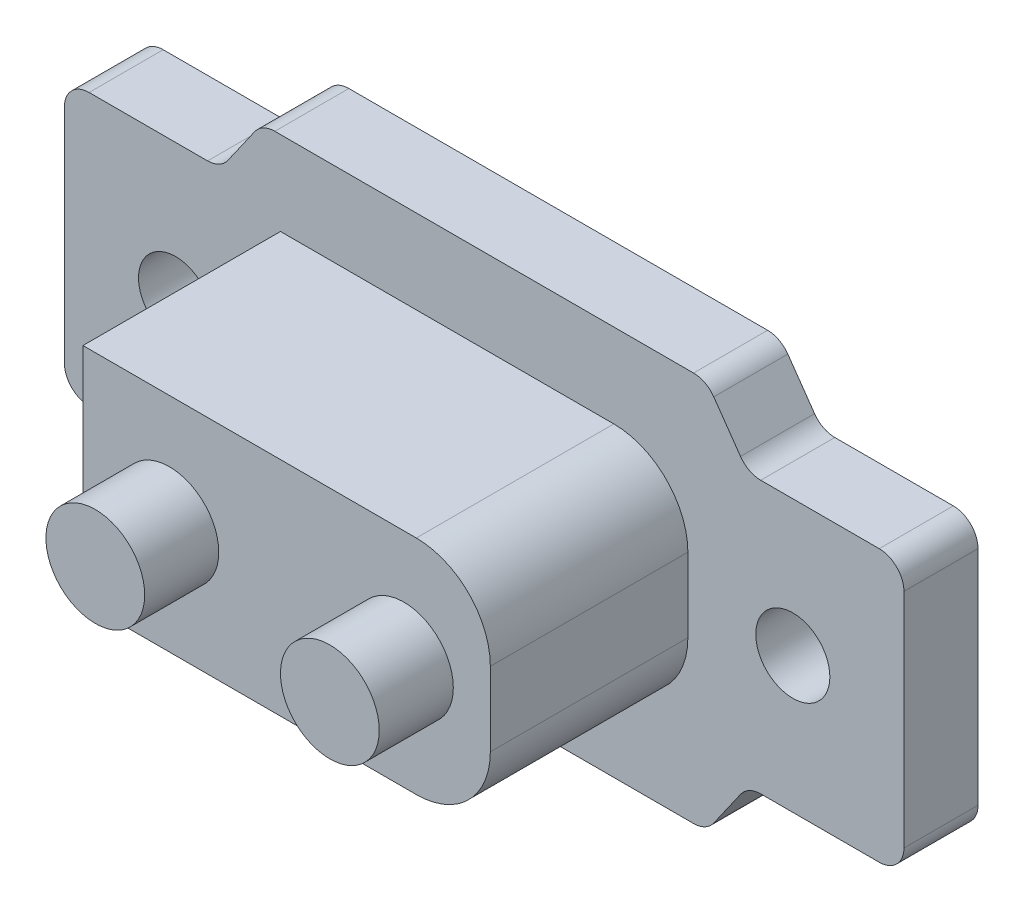
SolidWorks part; units mm, degrees
ref_plane "Front Plane" through (0, 0, 0) normal (0, 0, 1) x (1, 0, 0)
ref_plane "Top Plane" through (0, 0, 0) normal (0, 1, 0) x (1, 0, 0)
ref_plane "Right Plane" through (0, 0, 0) normal (1, 0, 0) x (0, 0, -1)
sketch "Sketch1" plane through (0, 0, 0) normal (0, 0, 1) x (1, 0, 0)
  line L1 (54.8017, 41.1928) -> (88.8017, 41.1928)
  line L2 (54.8017, 41.1928) -> (54.8017, 25.3928)
  line L3 (54.8017, 25.3928) -> (88.8017, 25.3928)
  line L4 (88.8017, 41.1928) -> (88.8017, 25.3928)
  dimension "D1" = 15.8
  dimension "D2" = 34
extrude "Boss-Extrude1" add sketch "Sketch1" along normal blind 3
sketch "Sketch2" plane through (0, 0, 3) normal (0, 0, 1) x (1, 0, 0)
  line L0 (54.8017, 33.2928) -> (88.8017, 33.2928) construction
  line L1 (54.8017, 41.1928) -> (54.8017, 25.3928) construction
  line L2 (88.8017, 25.3928) -> (88.8017, 41.1928) construction
  line L3 (71.8017, 41.1928) -> (71.8017, 25.3928) construction
  line L4 (88.8017, 41.1928) -> (54.8017, 41.1928) construction
  line L5 (54.8017, 25.3928) -> (88.8017, 25.3928) construction
  line L7 (63.5517, 37.7928) -> (77.0517, 37.7928)
  line L8 (63.5517, 37.7928) -> (63.5517, 28.7928)
  line L9 (63.5517, 28.7928) -> (77.0517, 28.7928)
  line L10 (80.0517, 34.7928) -> (80.0517, 31.7928)
  arc A0 (77.0517, 28.7928) -> (80.0517, 31.7928) centre (77.0517, 31.7928) ccw
  arc A1 (77.0517, 37.7928) -> (80.0517, 34.7928) centre (77.0517, 34.7928) cw
  point P18 (80.0517, 28.7928)
  point P21 (80.0517, 37.7928)
  dimension "D5" = 3
  dimension "D1" = 9
  dimension "D2" = 16.5
  dimension "D3" = 8.25
  dimension "D4" = 4.5
extrude "Boss-Extrude2" add sketch "Sketch2" along normal blind 8
sketch "Sketch3" plane through (0, 0, 3) normal (0, 0, 1) x (1, 0, 0)
  line L0 (54.8017, 33.2928) -> (88.8017, 33.2928) construction
  line L1 (54.8017, 41.1928) -> (62.8017, 41.1928)
  line L2 (54.8017, 41.1928) -> (54.8017, 38.7928)
  line L3 (54.8017, 38.7928) -> (61.1212, 38.7928)
  line L5 (54.8017, 41.1928) -> (54.8017, 25.3928) construction
  line L6 (88.8017, 25.3928) -> (88.8017, 41.1928) construction
  line L7 (62.8017, 41.1928) -> (61.1212, 38.7928)
  line L8 (71.8017, 41.1928) -> (71.8017, 25.3928) construction
  line L9 (88.8017, 41.1928) -> (54.8017, 41.1928) construction
  line L10 (54.8017, 25.3928) -> (88.8017, 25.3928) construction
  line L11 (62.8017, 25.3928) -> (61.1212, 27.7928)
  line L12 (54.8017, 27.7928) -> (61.1212, 27.7928)
  line L13 (54.8017, 25.3928) -> (54.8017, 27.7928)
  line L14 (54.8017, 25.3928) -> (62.8017, 25.3928)
  line L15 (88.8017, 25.3928) -> (80.8017, 25.3928)
  line L16 (88.8017, 25.3928) -> (88.8017, 27.7928)
  line L17 (88.8017, 27.7928) -> (82.4822, 27.7928)
  line L18 (80.8017, 25.3928) -> (82.4822, 27.7928)
  line L19 (80.8017, 41.1928) -> (82.4822, 38.7928)
  line L20 (88.8017, 38.7928) -> (82.4822, 38.7928)
  line L21 (88.8017, 41.1928) -> (88.8017, 38.7928)
  line L22 (88.8017, 41.1928) -> (80.8017, 41.1928)
  dimension "D1" = 5.5
  dimension "D2" = 8
  dimension "D3" = 55
extrude "Cut-Extrude1" cut sketch "Sketch3" against normal through all
sketch "Sketch4" plane through (0, 0, 11) normal (0, 0, 1) x (1, 0, 0)
  line L0 (71.8017, 41.1928) -> (71.8017, 25.3928) construction
  line L1 (80.8017, 41.1928) -> (62.8017, 41.1928) construction
  line L2 (62.8017, 25.3928) -> (80.8017, 25.3928) construction
  circle A0 centre (67.0517, 33.2928) radius 2
  circle A1 centre (76.5517, 33.2928) radius 2
  dimension "D1" = 4
  dimension "D2" = 4.75
  dimension "D3" = 4.75
extrude "Boss-Extrude3" add sketch "Sketch4" along normal blind 3
fillet "Fillet1" radius 1 12 edges at (88.8017, 38.7928, 1.5) (82.4822, 38.7928, 1.5) (80.8017, 41.1928, 1.5) (88.8017, 27.7928, 1.5) (82.4822, 27.7928, 1.5) (80.8017, 25.3928, 1.5) (62.8017, 25.3928, 1.5) (61.1212, 27.7928, 1.5) (54.8017, 27.7928, 1.5) (62.8017, 41.1928, 1.5) (61.1212, 38.7928, 1.5) (54.8017, 38.7928, 1.5)
sketch "Sketch5" plane through (0, 0, 3) normal (0, 0, 1) x (1, 0, 0)
  line L0 (71.8017, 41.1928) -> (71.8017, 25.3928) construction
  line L1 (80.2811, 41.1928) -> (63.3223, 41.1928) construction
  line L2 (63.3223, 25.3928) -> (80.2811, 25.3928) construction
  circle A0 centre (59.3017, 33.2928) radius 1.5
  circle A1 centre (84.3017, 33.2928) radius 1.5
extrude "Cut-Extrude2" cut sketch "Sketch5" against normal through all
sketch "Sketch6" plane through (0, 0, 0) normal (0, 0, -1) x (-1, 0, 0)
  line L0 (-71.8017, 41.1928) -> (-71.8017, 25.3928) construction
  line L1 (-77.8017, 36.7928) -> (-65.8017, 36.7928)
  line L2 (-79.8017, 34.7928) -> (-79.8017, 31.7928)
  line L3 (-77.8017, 29.7928) -> (-65.8017, 29.7928)
  line L4 (-63.8017, 34.7928) -> (-63.8017, 31.7928)
  line L5 (-80.2811, 41.1928) -> (-63.3223, 41.1928) construction
  line L6 (-63.3223, 25.3928) -> (-80.2811, 25.3928) construction
  line L7 (-88.8017, 33.2928) -> (-54.8017, 33.2928) construction
  line L8 (-88.8017, 28.7928) -> (-88.8017, 37.7928) construction
  line L9 (-54.8017, 37.7928) -> (-54.8017, 28.7928) construction
  arc A0 (-65.8017, 36.7928) -> (-63.8017, 34.7928) centre (-65.8017, 34.7928) cw
  arc A1 (-65.8017, 29.7928) -> (-63.8017, 31.7928) centre (-65.8017, 31.7928) ccw
  arc A2 (-79.8017, 31.7928) -> (-77.8017, 29.7928) centre (-77.8017, 31.7928) ccw
  arc A3 (-77.8017, 36.7928) -> (-79.8017, 34.7928) centre (-77.8017, 34.7928) ccw
  point P18 (-63.8017, 36.7928)
  point P23 (-79.8017, 29.7928)
  point P26 (-79.8017, 36.7928)
  dimension "D5" = 2
  dimension "D1" = 16
  dimension "D2" = 7
  dimension "D3" = 3.5
  dimension "D4" = 8
extrude "Cut-Extrude3" cut sketch "Sketch6" against normal blind 3
